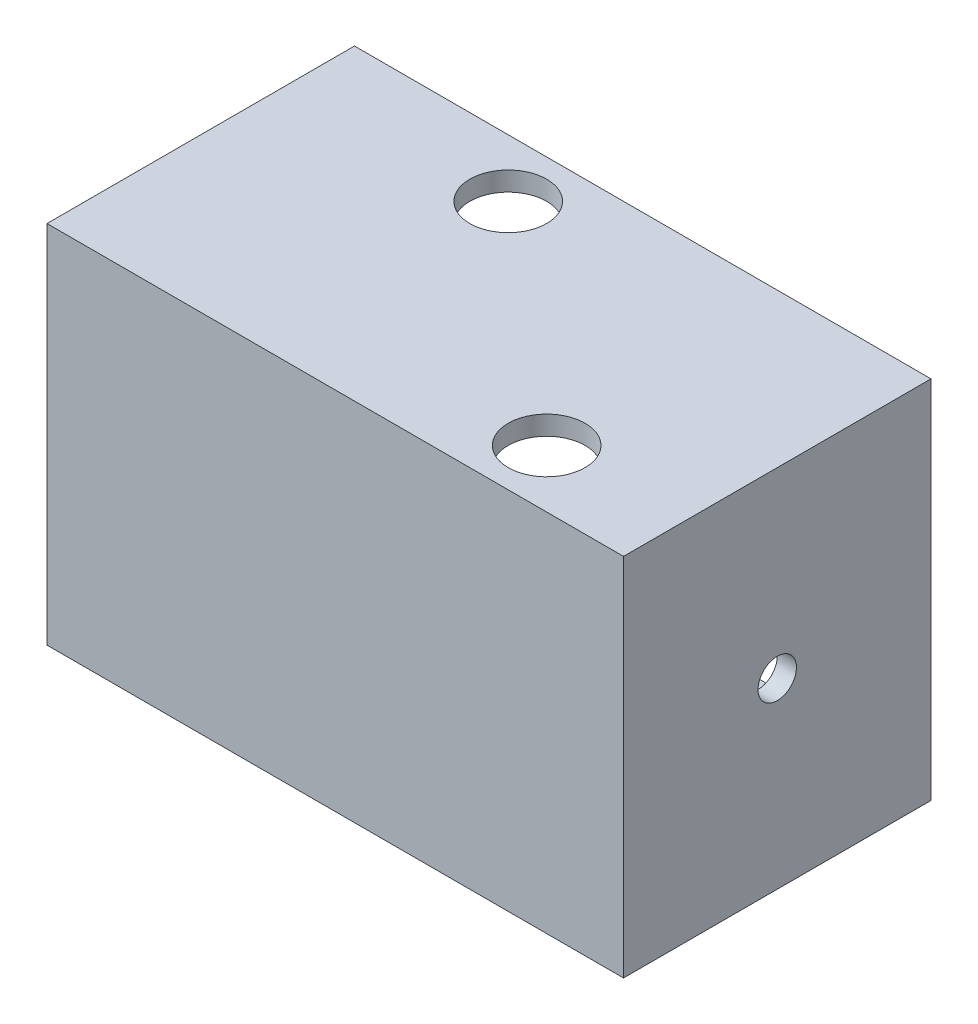
SolidWorks part; units mm, degrees
ref_plane "Plan de face" through (0, 0, 0) normal (0, 0, 1) x (1, 0, 0)
ref_plane "Plan de dessus" through (0, 0, 0) normal (0, 1, 0) x (1, 0, 0)
ref_plane "Plan de droite" through (0, 0, 0) normal (1, 0, 0) x (0, 0, -1)
sketch "Esquisse1" plane through (0, 0, 0) normal (0, 0, 1) x (1, 0, 0)
  line L1 (0, 0) -> (30, 0)
  line L2 (0, 0) -> (0, 19)
  line L3 (0, 19) -> (30, 19)
  line L4 (30, 0) -> (30, 19)
  dimension "D1" = 30
  dimension "D2" = 19
extrude "Boss.-Extru.1" add sketch "Esquisse1" along normal blind 16
sketch "Esquisse2" plane through (0, 0, 0) normal (-1, 0, 0) x (0, 0, 1)
  line L0 (8, 0) -> (8, 19) construction
  line L1 (16, 0) -> (0, 0) construction
  line L2 (16, 19) -> (0, 19) construction
  circle A0 centre (8, 9.5) radius 3
  dimension "D1" = 6
extrude "Enlèv. mat.-Extru.2" cut sketch "Esquisse2" against normal blind 29 contours A0
sketch "Esquisse3" plane through (30, 0, 0) normal (1, 0, 0) x (0, 0, -1)
  line L0 (-8, 0) -> (-8, 19) construction
  line L1 (-16, 0) -> (0, 0) construction
  line L2 (-16, 19) -> (0, 19) construction
  circle A0 centre (-8, 9.5) radius 1
  dimension "D1" = 2
extrude "Enlèv. mat.-Extru.3" cut sketch "Esquisse3" against normal blind 8
sketch "Esquisse7" plane through (0, 0, 0) normal (0, 0, -1) x (-1, 0, 0)
  line L0 (-30, 0) -> (-30, 19) construction
  line L1 (-29, 18) -> (-1, 18)
  line L2 (-29, 18) -> (-29, 1)
  line L3 (-29, 1) -> (-1, 1)
  line L4 (-1, 18) -> (-1, 1)
  line L5 (0, 19) -> (0, 0) construction
  line L6 (-30, 19) -> (0, 19) construction
  line L7 (0, 0) -> (-30, 0) construction
  dimension "D1" = 1
  dimension "D2" = 1
  dimension "D3" = 1
  dimension "D4" = 1
extrude "Enlèv. mat.-Extru.4" cut sketch "Esquisse7" against normal blind 15 contours L2 L1 L4 L3
sketch "Esquisse8" plane through (0, 19, 0) normal (0, 1, 0) x (1, 0, 0)
  line L0 (30, -16) -> (0, -16) construction
  line L2 (30, -16) -> (30, 0) construction
  circle A0 centre (23, -13) radius 2
  circle A1 centre (11, -3) radius 2
  dimension "D1" = 4
  dimension "D2" = 4
  dimension "D3" = 10
  dimension "D4" = 3
  dimension "D5" = 7
  dimension "D6" = 19
extrude "Enlèv. mat.-Extru.7" cut sketch "Esquisse8" against normal blind 1.5
